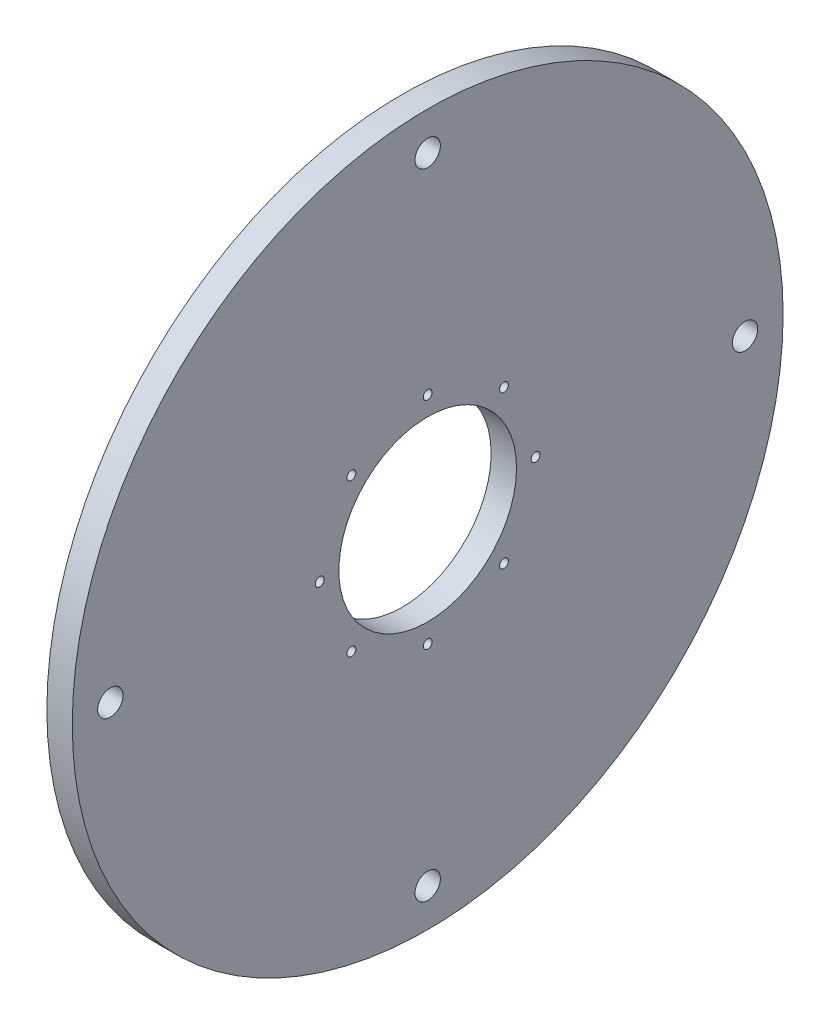
SolidWorks part; units mm, degrees
ref_plane "前视基准面" through (0, 0, 0) normal (0, 0, 1) x (1, 0, 0)
ref_plane "上视基准面" through (0, 0, 0) normal (0, 1, 0) x (1, 0, 0)
ref_plane "右视基准面" through (0, 0, 0) normal (1, 0, 0) x (0, 0, -1)
sketch "草图1" plane through (0, 0, 0) normal (1, 0, 0) x (0, 0, -1)
  circle A0 centre (-24.921, 0.0933) radius 140
  circle A1 centre (-24.921, 0.0933) radius 125
  circle A2 centre (-24.921, 0.0933) radius 35
  circle A3 centre (-24.921, 0.0933) radius 42.5
  circle A4 centre (-24.921, 42.5933) radius 1.75
  circle A9 centre (5.1311, 30.1454) radius 1.75
  circle A10 centre (17.579, 0.0933) radius 1.75
  circle A11 centre (5.1311, -29.9587) radius 1.75
  circle A12 centre (-24.921, -42.4067) radius 1.75
  circle A13 centre (-54.973, -29.9587) radius 1.75
  circle A14 centre (-67.421, 0.0933) radius 1.75
  circle A15 centre (-54.973, 30.1454) radius 1.75
  circle A17 centre (-149.921, 0.0933) radius 5
  circle A18 centre (-24.921, 125.0933) radius 5
  circle A19 centre (100.079, 0.0933) radius 5
  circle A20 centre (-24.921, -124.9067) radius 5
  point P9 (0, 0)
  point P10 (0, 0)
  point P11 (0, 0)
  point P18 (-24.921, 0.0933)
  point P33 (-24.921, 0.0933)
  point P34 (0, 0)
  point P35 (0, 0)
  point P36 (-24.921, 0.0933)
  dimension "D1" = 4
  dimension "D3" = 85
  dimension "D5" = 250
  dimension "D6" = 280
  dimension "D4" = 42.5
  dimension "D2" = 8
extrude "凸台-拉伸1" add sketch "草图1" along normal blind 10 contours A0 A20 A1 A17 A18 A19 | A20 A1 A19 A18 A17 A15 A3 A4 A9 A10 A11 A12 A13 A14 | A15 A3 A14 A13 A12 A11 A10 A9 A4 A2
